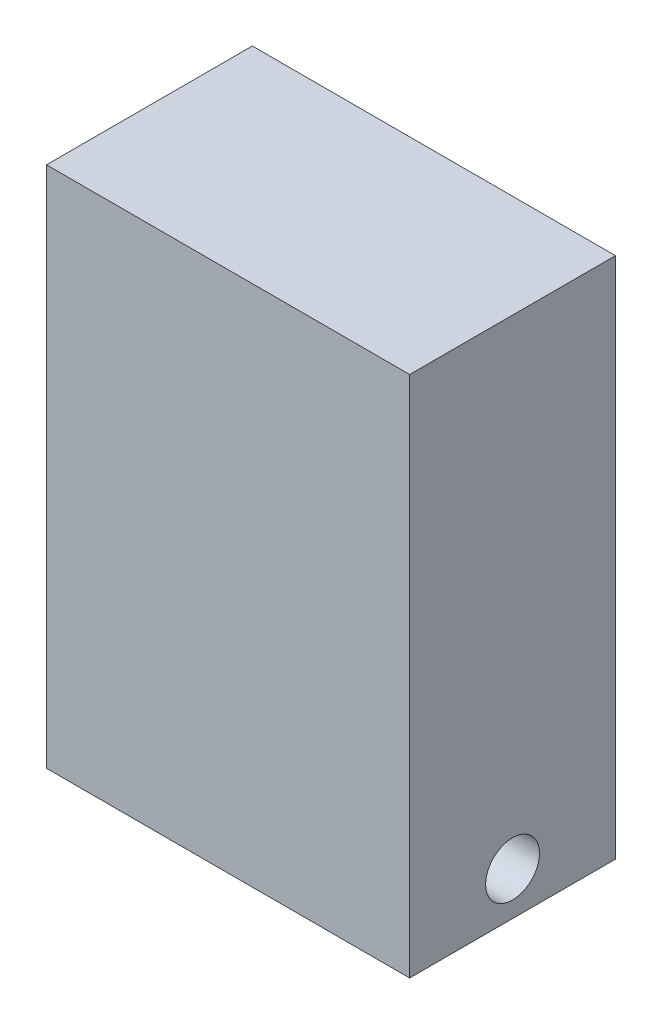
SolidWorks part; units mm, degrees
ref_plane "Front Plane" through (0, 0, 0) normal (0, 0, 1) x (1, 0, 0)
ref_plane "Top Plane" through (0, 0, 0) normal (0, 1, 0) x (1, 0, 0)
ref_plane "Right Plane" through (0, 0, 0) normal (1, 0, 0) x (0, 0, -1)
sketch "Sketch2" plane through (0, 0, 0) normal (0, 0, 1) x (1, 0, 0)
  line L1 (0, 0) -> (85.598, 0)
  line L2 (0, 0) -> (0, 123.19)
  line L3 (0, 123.19) -> (85.598, 123.19)
  line L4 (85.598, 0) -> (85.598, 123.19)
  dimension "D1" = 123.19
  dimension "D2" = 85.598
extrude "Boss-Extrude1" add sketch "Sketch2" along normal blind 48.514
sketch "Sketch3" plane through (0, 0, 0) normal (-1, 0, 0) x (0, 0, 1)
  line L0 (24.257, 0) -> (24.257, 10.16) construction
  line L1 (48.514, 0) -> (0, 0) construction
  circle A0 centre (24.257, 10.16) radius 6.35
  dimension "D1" = 12.7
extrude "Cut-Extrude1" cut sketch "Sketch3" against normal through all both and the other way through all
sketch "Sketch5" plane through (0, 0, 0) normal (-1, 0, 0) x (0, 0, 1)
  line L0 (0, 61.595) -> (48.514, 61.595)
  line L1 (0, 123.19) -> (0, 0) construction
  line L2 (48.514, 123.19) -> (48.514, 0) construction
  text T0 "DC 12 V (Fluid Exit)"
sketch "Sketch6" plane through (0, 0, 48.514) normal (0, 0, 1) x (1, 0, 0)
  line L0 (0, 61.595) -> (85.598, 61.595)
  line L1 (0, 123.19) -> (0, 0) construction
  line L2 (85.598, 0) -> (85.598, 123.19) construction
sketch "Sketch7" plane through (85.598, 0, 0) normal (1, 0, 0) x (0, 0, -1)
  line L0 (-48.514, 61.595) -> (0, 61.595)
  text T0 "Fluid Entrance"
